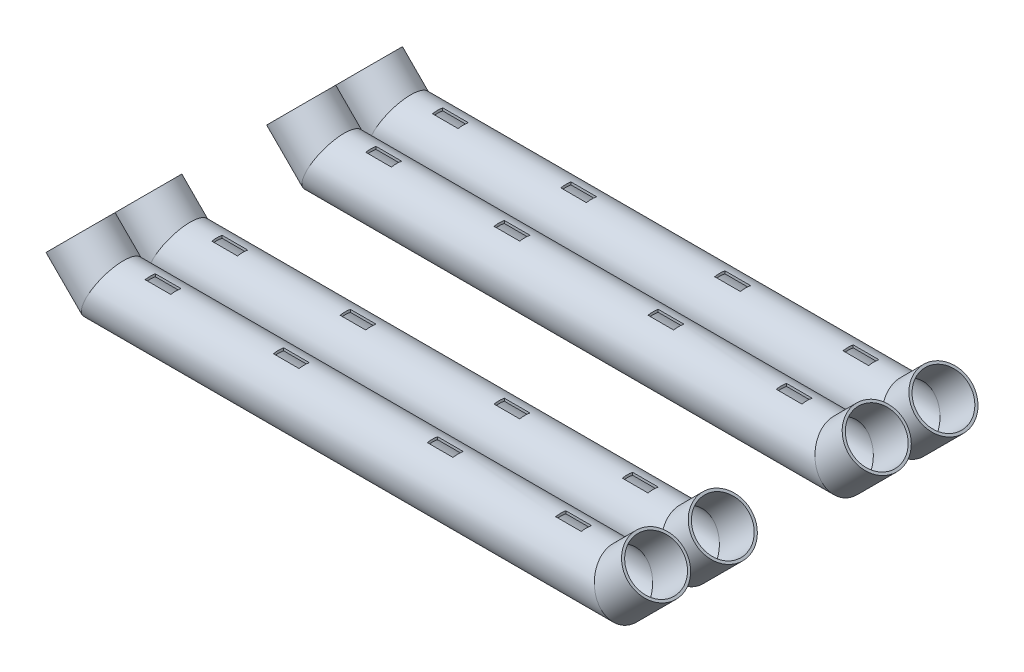
SolidWorks part; units mm, degrees
ref_plane "Спереди" through (0, 0, 0) normal (0, 0, 1) x (1, 0, 0)
ref_plane "Сверху" through (0, 0, 0) normal (0, 1, 0) x (1, 0, 0)
ref_plane "Справа" through (0, 0, 0) normal (1, 0, 0) x (0, 0, -1)
sketch "Эскиз2" plane through (0, 0, 0) normal (0, 1, 0) x (1, 0, 0)
  line L0 (0, 0) -> (-1000, 0) construction
  line L1 (-500, -255) -> (-500, 255) construction
  point P5 (-500, 0)
  point P6 (-500, 0)
  dimension "D1" = 1000
  dimension "D2" = 510
ref_plane "Плоскость1" through (0, 0, 150) normal (0, 0, 1) x (1, 0, 0)
sketch "Эскиз4" plane through (0, 0, 150) normal (0, 0, 1) x (1, 0, 0)
  line L0 (-1000, 0) -> (0, 0)
  line L1 (0, 0) -> (-1000, 0) construction
  line L2 (0, 0) -> (60.8112, 60.8112)
  line L3 (-1000, 0) -> (-1060.8112, 60.8112)
  dimension "D1" = 135
  dimension "D2" = 86
  dimension "D3" = 1000
ref_plane "Плоскость5" through (0, 0, -150) normal (0, 0, 1) x (1, 0, 0)
sketch "Эскиз7" plane through (0, 0, -150) normal (0, 0, 1) x (1, 0, 0)
  line L0 (-1060.8112, 60.8112) -> (-1000, 0)
  line L1 (-1000, 0) -> (0, 0)
  line L2 (0, 0) -> (60.8112, 60.8112)
sketch "Эскиз8" plane through (0, 0, 0) normal (1, 0, 0) x (0, 0, -1)
  circle A0 centre (-150, 0) radius 55
  circle A1 centre (-150, 0) radius 50
  dimension "D1" = 110
  dimension "D2" = 100
sweep "По траектории2" add profiles "Эскиз8" path "Эскиз4"
sketch "Эскиз9" plane through (0, 0, 0) normal (1, 0, 0) x (0, 0, -1)
  line L0 (-255, 0) -> (255, 0) construction
  line L1 (150, 60.8112) -> (150, 0) construction
  circle A0 centre (150, 0) radius 55
  circle A1 centre (150, 0) radius 50
  dimension "D1" = 110
  dimension "D2" = 100
sweep "По траектории3" add profiles "Эскиз9" path "Эскиз7"
sketch "Эскиз10" plane through (0, 0, 0) normal (0, 1, 0) x (1, 0, 0)
  line L0 (-188.8057, 150) -> (188.8057, 150) construction
  line L1 (-925, 140) -> (-875, 140)
  line L2 (-925, 140) -> (-925, 160)
  line L3 (-925, 160) -> (-875, 160)
  line L4 (-875, 140) -> (-875, 160)
  line L5 (-925, 140) -> (-875, 160) construction
  line L6 (-925, 160) -> (-875, 140) construction
  line L7 (-500, -255) -> (-500, 255) construction
  line L8 (-500, 255) -> (-500, -255) construction
  line L9 (0, 0) -> (-1000, 0) construction
  line L10 (-75, 140) -> (-125, 140)
  line L11 (-75, 140) -> (-75, 160)
  line L12 (-75, 160) -> (-125, 160)
  line L13 (-125, 140) -> (-125, 160)
  line L14 (-125, -140) -> (-125, -160)
  line L15 (-75, -160) -> (-125, -160)
  line L16 (-75, -140) -> (-75, -160)
  line L17 (-75, -140) -> (-125, -140)
  line L18 (-925, -140) -> (-925, -160)
  line L19 (-925, -160) -> (-875, -160)
  line L20 (-875, -140) -> (-875, -160)
  line L21 (-925, -140) -> (-875, -140)
  line L22 (-325, 140) -> (-325, 160)
  line L23 (-675, 140) -> (-625, 140)
  line L24 (-675, 140) -> (-675, 160)
  line L25 (-675, 160) -> (-625, 160)
  line L26 (-625, 140) -> (-625, 160)
  line L27 (-675, 140) -> (-625, 160) construction
  line L28 (-675, 160) -> (-625, 140) construction
  line L29 (-325, 160) -> (-375, 160)
  line L30 (-375, 140) -> (-375, 160)
  line L31 (-325, 140) -> (-375, 140)
  line L32 (-375, -140) -> (-375, -160)
  line L33 (-325, -160) -> (-375, -160)
  line L34 (-325, -140) -> (-325, -160)
  line L35 (-325, -140) -> (-375, -140)
  line L36 (-625, -140) -> (-625, -160)
  line L37 (-675, -160) -> (-625, -160)
  line L38 (-675, -140) -> (-675, -160)
  line L39 (-675, -140) -> (-625, -140)
  point P0 (-900, 150)
  point P29 (-650, 150)
  dimension "D1" = 50
  dimension "D2" = 20
  dimension "D3" = 400
  dimension "D4" = 250
extrude "Вырез-Вытянуть2" cut sketch "Эскиз10" along normal up to next
ref_plane "Плоскость6" through (0, 0, 280) normal (0, 0, 1) x (1, 0, 0)
ref_plane "Плоскость7" through (0, 0, -280) normal (0, 0, 1) x (1, 0, 0)
sketch "Эскиз11" plane through (0, 0, -280) normal (0, 0, 1) x (1, 0, 0)
  line L0 (-1060.8112, 60.8112) -> (-1000, 0)
  line L1 (-1021.9203, 99.7021) -> (-1099.7021, 21.9203) construction
  line L2 (0, 0) -> (-1000, 0) construction
  line L3 (-1000, 0) -> (0, 0)
  line L4 (0, 0) -> (60.8112, 60.8112)
  line L5 (99.7021, 21.9203) -> (21.9203, 99.7021) construction
sketch "Эскиз12" plane through (0, 0, 0) normal (1, 0, 0) x (0, 0, -1)
  line L0 (280, 0) -> (280, 60.8112) construction
  line L1 (280, 188.8057) -> (280, -188.8057) construction
  line L2 (0, 85.0861) -> (0, -85.0861) construction
  circle A0 centre (280, 0) radius 55
  circle A1 centre (-280, 0) radius 55
  circle A2 centre (280, 0) radius 50
  circle A3 centre (-280, 0) radius 50
  dimension "D1" = 110
  dimension "D2" = 100
sweep "По траектории4" add profiles "Эскиз12" path "Эскиз11"
sketch "Эскиз13" plane through (0, 0, 0) normal (0, 1, 0) x (1, 0, 0)
  line L0 (-188.8057, 280) -> (188.8057, 280) construction
  line L1 (-925, 270) -> (-875, 270)
  line L2 (-925, 270) -> (-925, 290)
  line L3 (-925, 290) -> (-875, 290)
  line L4 (-875, 270) -> (-875, 290)
  line L5 (-925, 270) -> (-875, 290) construction
  line L6 (-925, 290) -> (-875, 270) construction
  line L8 (-675, 270) -> (-625, 270)
  line L9 (-675, 270) -> (-675, 290)
  line L10 (-675, 290) -> (-625, 290)
  line L11 (-625, 270) -> (-625, 290)
  line L12 (-675, 270) -> (-625, 290) construction
  line L13 (-675, 290) -> (-625, 270) construction
  line L14 (-500, 255) -> (-500, -255) construction
  line L15 (-1000, 0) -> (0, 0) construction
  line L16 (-375, 270) -> (-375, 290)
  line L17 (-325, 290) -> (-375, 290)
  line L18 (-325, 270) -> (-325, 290)
  line L19 (-325, 270) -> (-375, 270)
  line L20 (-75, 270) -> (-75, 290)
  line L21 (-125, 270) -> (-125, 290)
  line L22 (-75, 290) -> (-125, 290)
  line L23 (-75, 270) -> (-125, 270)
  line L24 (-125, -270) -> (-125, -290)
  line L25 (-75, -290) -> (-125, -290)
  line L26 (-75, -270) -> (-75, -290)
  line L27 (-75, -270) -> (-125, -270)
  line L28 (-375, -270) -> (-375, -290)
  line L29 (-325, -290) -> (-375, -290)
  line L30 (-325, -270) -> (-325, -290)
  line L31 (-325, -270) -> (-375, -270)
  line L32 (-625, -270) -> (-625, -290)
  line L33 (-675, -290) -> (-625, -290)
  line L34 (-675, -270) -> (-675, -290)
  line L35 (-675, -270) -> (-625, -270)
  line L36 (-925, -270) -> (-925, -290)
  line L37 (-925, -290) -> (-875, -290)
  line L38 (-875, -270) -> (-875, -290)
  line L39 (-925, -270) -> (-875, -270)
  point P0 (-900, 280)
  point P7 (-650, 280)
  dimension "D1" = 50
  dimension "D2" = 20
extrude "Вырез-Вытянуть4" cut sketch "Эскиз13" along normal blind 60
